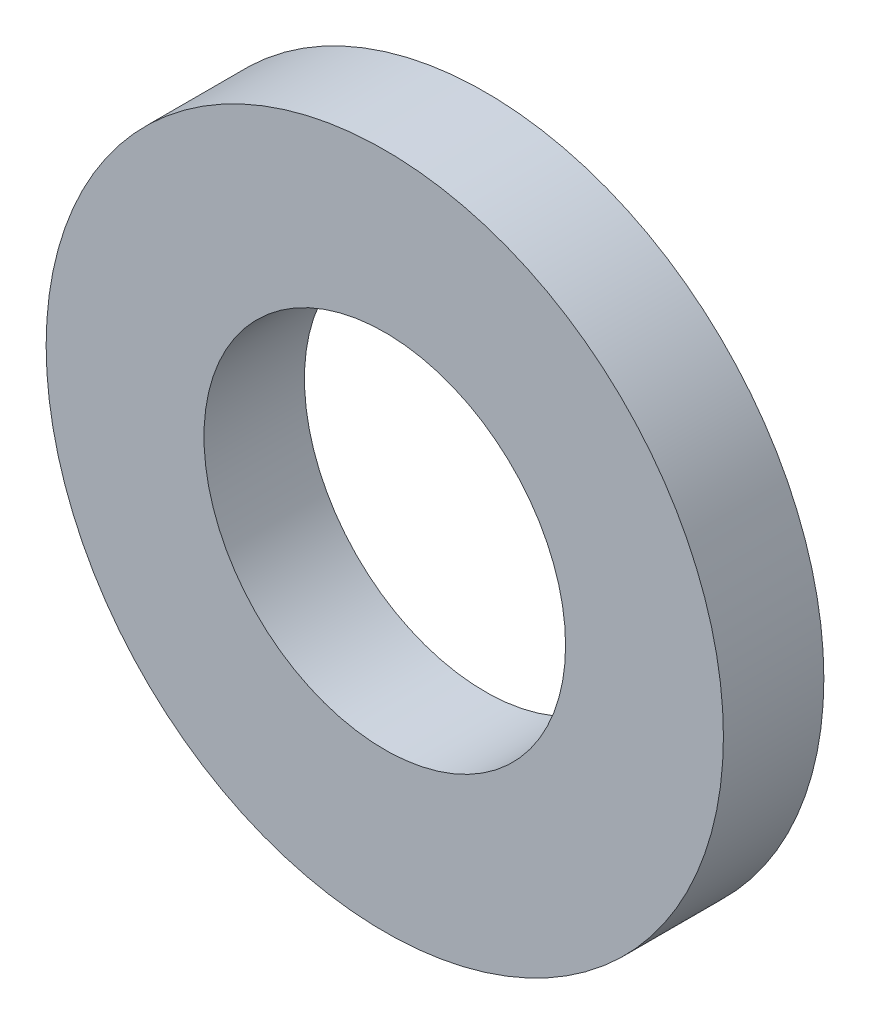
SolidWorks part; units mm, degrees
ref_plane "Front Plane" through (0, 0, 0) normal (0, 0, 1) x (1, 0, 0)
ref_plane "Top Plane" through (0, 0, 0) normal (0, 1, 0) x (1, 0, 0)
ref_plane "Right Plane" through (0, 0, 0) normal (1, 0, 0) x (0, 0, -1)
sketch "Sketch1" plane through (0, 0, 0) normal (0, 0, 1) x (1, 0, 0)
  circle A0 centre (0, 0) radius 5.9944
  circle A1 centre (0, 0) radius 3.2004
  point P5 (0, -5.9944)
  dimension "OD" = 11.9888
  dimension "ID" = 6.4008
sketch "Sketch2" plane through (0, 0, 0) normal (1, 0, 0) x (0, 0, -1)
  line L0 (-0.889, 0) -> (0.889, 0) construction
  point P0 (-0.889, -5.9944)
  point P4 (0, 0)
  point P6 (0.889, -5.9944)
  dimension "Thickness Range" = 1.778
sketch "Sketch3" plane through (0, 0, 0) normal (0, 0, 1) x (1, 0, 0)
  circle A0 centre (0, 0) radius 5.9944 construction
  circle A1 centre (0, 0) radius 3.2004 construction
  circle A2 centre (0, 0) radius 5.9944
  circle A3 centre (0, 0) radius 3.2004
extrude "Boss-Extrude1" add sketch "Sketch3" along normal up to vertex (0.889 mm away) and the other way up to vertex (0.889 mm away) up to point (0, -5.9944, 0.889) other way up to point (0, -5.9944, -0.889)
